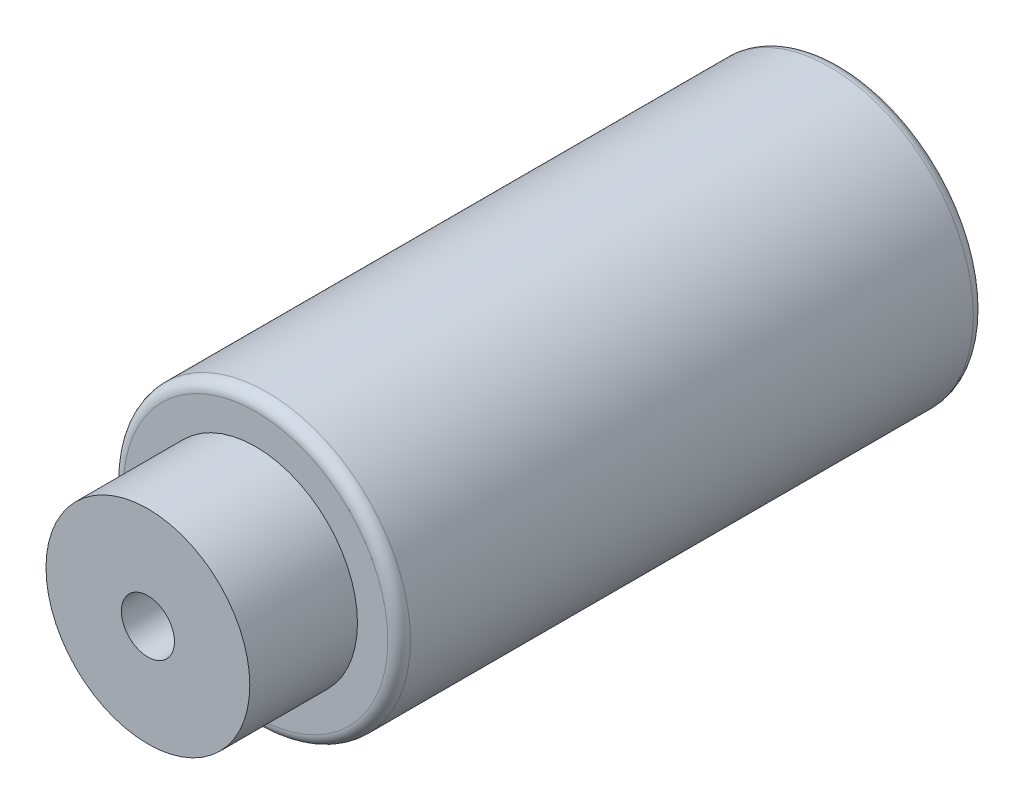
SolidWorks part; units mm, degrees
material "Brass"
ref_plane "Front Plane" through (0, 0, 0) normal (0, 0, 1) x (1, 0, 0)
ref_plane "Top Plane" through (0, 0, 0) normal (0, 1, 0) x (1, 0, 0)
ref_plane "Right Plane" through (0, 0, 0) normal (1, 0, 0) x (0, 0, -1)
ref_plane "Plane1" through (0, 0, 4) normal (0, 0, 1) x (1, 0, 0)
sketch "Sketch1" plane through (0, 0, 0) normal (0, 0, 1) x (1, 0, 0)
  circle A0 centre (0, 0) radius 12.7
  dimension "D1" = 25.4
extrude "Boss-Extrude1" add sketch "Sketch1" along normal blind 51.816
fillet "Fillet1" radius 1 2 edges at (12.7, 0, 0) (12.7, 0, 51.816)
sketch "Sketch2" plane through (0, 0, 51.816) normal (0, 0, 1) x (1, 0, 0)
  circle A0 centre (0, 0) radius 9.017
  dimension "D1" = 18.034
sketch "Sketch5" plane through (0, 0, 0) normal (0, 0, -1) x (-1, 0, 0)
  circle A0 centre (0, 0) radius 5.4991
  dimension "D1" = 10.9982
extrude "Boss-Extrude3" add sketch "Sketch2" along normal blind 9.53
sketch "Sketch6" plane through (0, 0, 61.346) normal (0, 0, 1) x (1, 0, 0)
  circle A0 centre (0, 0) radius 2.3495
  dimension "D1" = 4.699
extrude "Cut-Extrude1" cut sketch "Sketch5" against normal blind 50.8 contours A0
extrude "Cut-Extrude2" cut sketch "Sketch6" against normal blind 50.8 contours A0
